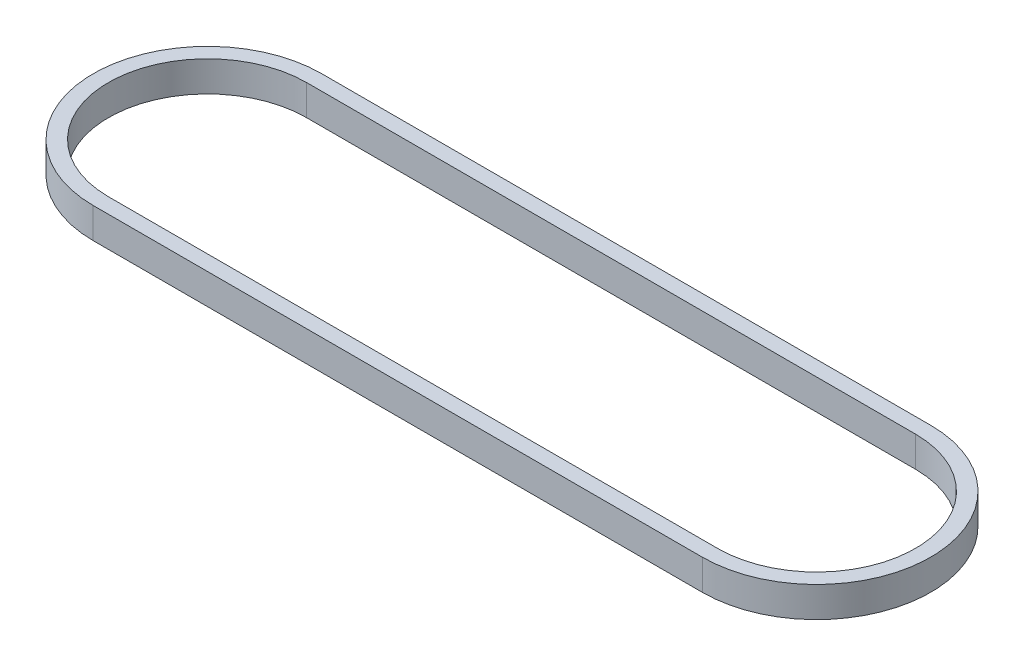
SolidWorks part; units mm, degrees
material "1023 Carbon Steel Sheet (SS)"
ref_plane "Front Plane" through (0, 0, 0) normal (0, 0, 1) x (1, 0, 0)
ref_plane "Top Plane" through (0, 0, 0) normal (0, 1, 0) x (1, 0, 0)
ref_plane "Right Plane" through (0, 0, 0) normal (1, 0, 0) x (0, 0, -1)
sketch "Sketch1" plane through (0, 0, 0) normal (0, 1, 0) x (1, 0, 0)
  line L0 (-40, 0) -> (40, 0) construction
  line L1 (-40, 13) -> (40, 13)
  line L2 (-40, -13) -> (40, -13)
  line L3 (-40, 15) -> (40, 15)
  line L4 (-40, -15) -> (40, -15)
  arc A0 (-40, 13) -> (-40, -13) centre (-40, 0) ccw
  arc A1 (40, -13) -> (40, 13) centre (40, 0) ccw
  arc A2 (40, -15) -> (40, 15) centre (40, 0) ccw
  arc A3 (-40, 15) -> (-40, -15) centre (-40, 0) ccw
  point P3 (0, 0)
  point P14 (0, 0)
  point P15 (0, 0)
  dimension "D3" = 13
  dimension "D2" = 80
  dimension "D1" = 2
extrude "Boss-Extrude1" add sketch "Sketch1" along normal blind 4
